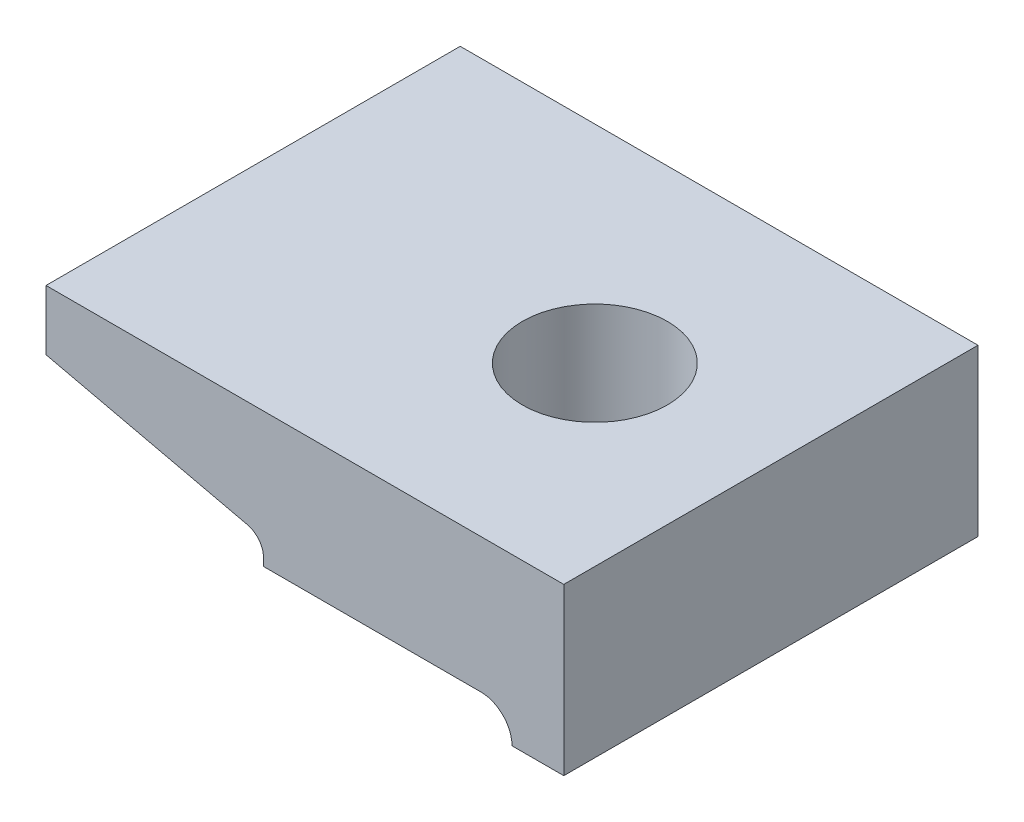
SolidWorks part; units mm, degrees
material "SS400"
ref_plane "Front" through (0, 0, 0) normal (0, 0, 1) x (1, 0, 0)
ref_plane "Top" through (0, 0, 0) normal (0, 1, 0) x (1, 0, 0)
ref_plane "Right" through (0, 0, 0) normal (1, 0, 0) x (0, 0, -1)
sketch "ｽｹｯﾁ3" plane through (0, 0, 0) normal (0, 0, 1) x (1, 0, 0)
  line B0 (0, 0) -> (0, 96.66) construction
  line B1 (46.83, 4.5937) -> (46.83, 1.59)
  line B2 (11.0471, 14.1196) -> (45.5977, 6.1429)
  line B3 (-11.0471, 14.1196) -> (-45.5977, 6.1429)
  line B4 (-45.24, 0) -> (45.24, 0)
  arc B5 (45.24, 0) -> (46.83, 1.59) centre (45.24, 1.59) ccw
  arc B6 (46.83, 4.5937) -> (45.5977, 6.1429) centre (45.24, 4.5937) ccw
  arc B7 (6.1419, 19.8523) -> (11.0471, 14.1196) centre (12.4756, 20.3068) ccw
  arc B8 (-11.0471, 14.1196) -> (-6.1419, 19.8523) centre (-12.4756, 20.3068) ccw
  arc B9 (17.927, 96.1323) -> (-17.927, 96.1323) centre (0, -208.14) ccw
sketch_block_instance "RAIL-22K-1"
sketch_block "RAIL-22K" parameters "D1"=1.59, "D5"=1.59, "D6"=1.59, "D7"=6.35, "D10"=304.8, "D12"=7.94, "D16"=304.8, "D17"=6.35, "D23"=1.59, "D2"=13, "D3"=46.83, "D4"=93.66, "D8"=41.67, "D9"=96.66, "D11"=50.8, "D13"=77, "D14"=20.3068, "D15"=12.4756, "D18"=63.0332, "D19"=13, "D20"=12.4756, "D21"=41.67, "D22"=77, "D24"=25.4
sketch "ｽｹｯﾁ1" plane through (0, 0, 0) normal (0, 0, 1) x (1, 0, 0)
  line L0 (73, 0) -> (78, 0)
  line L1 (78, 0) -> (78, 16)
  line L2 (78, 16) -> (28, 16)
  line L3 (28, 16) -> (28, 10.2057)
  line L4 (28, 10.2057) -> (47.4499, 5.7154)
  line L5 (49, 3.7666) -> (49, 3)
  line L6 (49, 3) -> (70, 3)
  line L8 (61, 16) -> (61, 3) construction
  line L9 (50, 0) -> (-50, 0) construction
  line L10 (0, 0) -> (0, 96.66) construction
  arc A0 (47.4499, 5.7154) -> (49, 3.7666) centre (47, 3.7666) cw
  arc A1 (73, 0) -> (70, 3) centre (70, 0) ccw
  point P15 (49, 5.3575)
  dimension "D10" = 2
  dimension "D11" = 6
  dimension "D1" = 61
  dimension "D2" = 17
  dimension "D3" = 50
  dimension "D4" = 13
  dimension "D5" = 3
  dimension "D6" = 21
  dimension "D7" = 5.3575
  dimension "D8" = 5
  dimension "D9" = 16
  dimension "D12" = 49
extrude "ﾎﾞｽ - 押し出し1" add sketch "ｽｹｯﾁ1" along normal mid plane 40
sketch "ｽｹｯﾁ2" plane through (0, 16, 0) normal (0, 1, 0) x (1, 0, 0)
  line L0 (-50, 0) -> (50, 0) construction
  line L1 (78, -20) -> (78, 20) construction
  circle A0 centre (61, 0) radius 7
  point P2 (0, 0)
  point P5 (0, 0)
  dimension "D1" = 14
  dimension "D2" = 17
extrude "ｶｯﾄ - 押し出し1" cut sketch "ｽｹｯﾁ2" against normal through all
